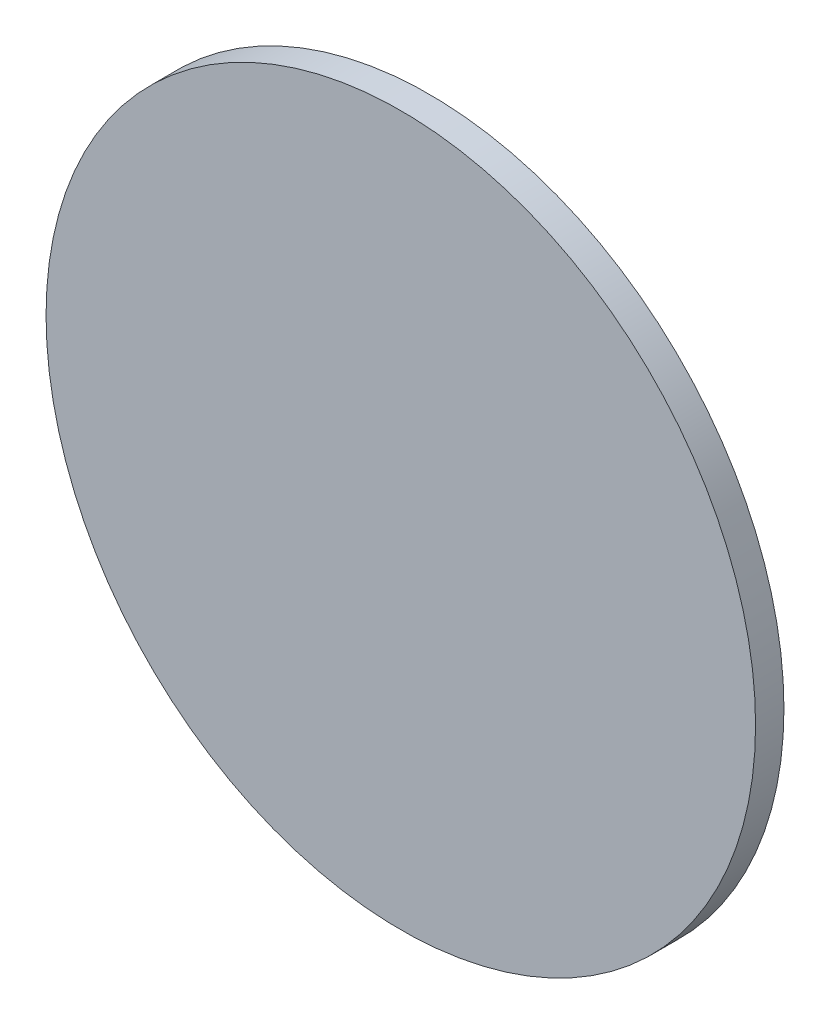
SolidWorks part; units mm, degrees
ref_plane "正面" through (0, 0, 0) normal (0, 0, 1) x (1, 0, 0)
ref_plane "平面" through (0, 0, 0) normal (0, 1, 0) x (1, 0, 0)
ref_plane "右側面" through (0, 0, 0) normal (1, 0, 0) x (0, 0, -1)
sketch "ｽｹｯﾁ1" plane through (0, 0, 0) normal (0, 0, 1) x (1, 0, 0)
  circle A0 centre (0, 0) radius 12.5
  dimension "D1" = 25
extrude "ﾎﾞｽ - 押し出し1" add sketch "ｽｹｯﾁ1" along normal mid plane 1
